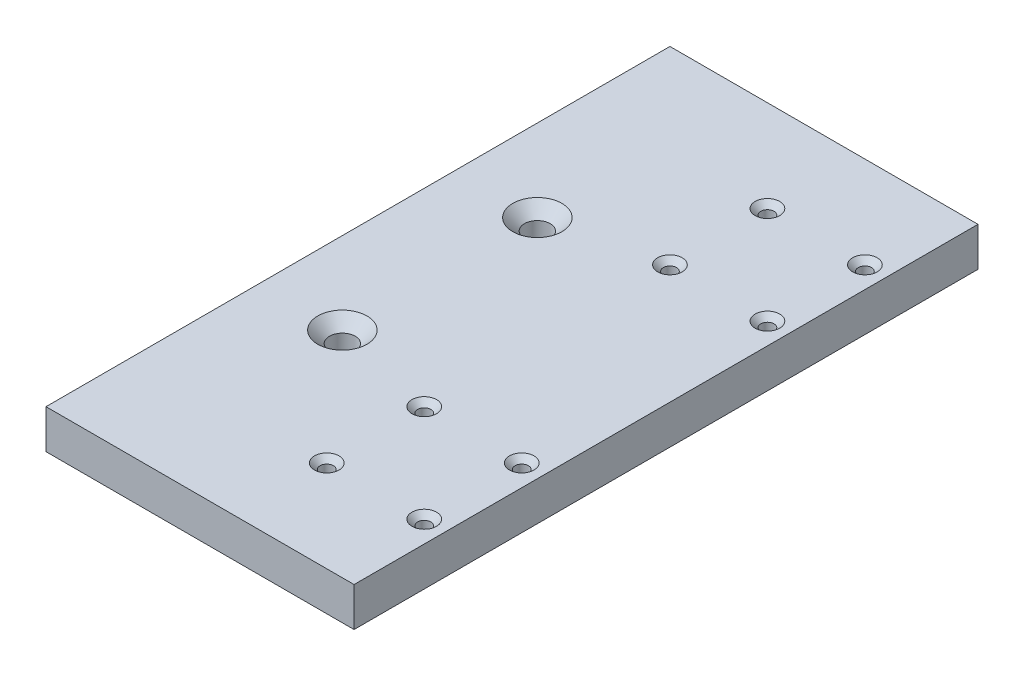
SolidWorks part; units mm, degrees
material "3.1355 (EN-AW 2024)"
ref_plane "Спереди" through (0, 0, 0) normal (0, 0, 1) x (1, 0, 0)
ref_plane "Сверху" through (0, 0, 0) normal (0, 1, 0) x (1, 0, 0)
ref_plane "Справа" through (0, 0, 0) normal (1, 0, 0) x (0, 0, -1)
sketch "Эскиз1" plane through (0, 0, 0) normal (0, 1, 0) x (1, 0, 0)
  line L1 (-39.5, 80) -> (39.5, 80)
  line L2 (-39.5, 80) -> (-39.5, -80)
  line L3 (-39.5, -80) -> (39.5, -80)
  line L4 (39.5, 80) -> (39.5, -80)
  line L5 (-39.5, 80) -> (39.5, -80) construction
  line L6 (-39.5, -80) -> (39.5, 80) construction
  point P0 (0, 0)
  dimension "D1" = 160
  dimension "D2" = 79
extrude "База" add sketch "Эскиз1" along normal blind 10
hole_wizard "Каретки M3" positions "Эскиз2" profile "Эскиз3" countersink size "M3" standard "DIN" end condition through all
sketch "Эскиз2" plane through (0, 10, 0) normal (0, 1, 0) x (1, 0, 0)
  line L0 (9, -31.5) -> (21.5, -31.5) construction
  line L1 (21.5, -31.5) -> (34, -31.5) construction
  line L2 (34, -31.5) -> (34, -56.5) construction
  line L5 (-50, 0) -> (50, 0) construction
  line L6 (34, 31.5) -> (34, 56.5) construction
  line L7 (21.5, 31.5) -> (34, 31.5) construction
  line L8 (9, 31.5) -> (21.5, 31.5) construction
  line L9 (39.5, -80) -> (39.5, 80) construction
  point P0 (9, -56.5)
  point P2 (34, -56.5)
  point P4 (34, -31.5)
  point P6 (9, -31.5)
  point P23 (9, 56.5)
  point P27 (9, 31.5)
  point P30 (34, 31.5)
  point P33 (34, 56.5)
  point P34 (9, 56.5)
  point P35 (34, -44)
  dimension "D1" = 25
  dimension "D2" = 25
  dimension "D3" = 44
  dimension "D4" = 18
sketch "Эскиз3" plane through (9, 10, 56.5) normal (1, 0, 0) x (0, 0, 1)
  line L0 (0, 0) -> (0, 10)
  line L1 (0, 10) -> (1.7, 10)
  line L2 (1.7, 10) -> (1.7, 1.45)
  line L3 (1.7, 1.45) -> (3.15, 0)
  line L5 (3.15, 0) -> (0, 0)
  line L6 (-1.7, 1.45) -> (-3.15, 0) construction
  line L11 (0, -6.35) -> (0, 107.95) construction
  dimension "Диаметр сквозного отверстия" = 3.4
  dimension "Глубина сквозного отверстия" = 10
  dimension "Диаметр передней зенковки" = 6.3
  dimension "Угол передней зенковки" = 90
hole_wizard "КреплениеПлиты-M6" positions "Эскиз6" profile "Эскиз7" countersink size "M6" standard "ISO" end condition through all
sketch "Эскиз6" plane through (0, 10, 0) normal (0, 1, 0) x (1, 0, 0)
  line L0 (-18.5, 25) -> (-18.5, 0) construction
  line L1 (-18.5, 0) -> (-18.5, -25) construction
  line L2 (39.5, -80) -> (39.5, 80) construction
  point P2 (-18.5, 25)
  point P5 (-18.5, -25)
  dimension "D1" = 58
  dimension "D2" = 25
sketch "Эскиз7" plane through (-18.5, 10, -25) normal (1, 0, 0) x (0, 0, 1)
  line L0 (0, 0) -> (0, 10)
  line L1 (0, 10) -> (3.3, 10)
  line L2 (3.3, 10) -> (3.3, 3)
  line L3 (3.3, 3) -> (6.3, 0)
  line L5 (6.3, 0) -> (0, 0)
  line L6 (-3.3, 3) -> (-6.3, 0) construction
  line L11 (0, -6.35) -> (0, 107.95) construction
  dimension "Диаметр сквозного отверстия" = 6.6
  dimension "Глубина сквозного отверстия" = 10
  dimension "Диаметр передней зенковки" = 12.6
  dimension "Угол передней зенковки" = 90
hole_wizard "Отверстие обработанное метчиком M61" positions "Эскиз8" profile "Эскиз10" tap size "M6" standard "DIN"
sketch "Эскиз8" plane through (-39.5, 0, 0) normal (-1, 0, 0) x (0, 0, 1)
  line L1 (-40, 5) -> (0, 5) construction
  line L2 (0, 5) -> (40, 5) construction
  line L5 (-80, 10) -> (-80, 0) construction
  point P0 (-40, 5)
  point P3 (40, 5)
  point P19 (-80, 5)
  dimension "D1" = 80
sketch "Эскиз10" plane through (-39.5, 5, -40) normal (0, 1, 0) x (0, 0, 1)
  line L0 (0, 0) -> (0, 36.5022)
  line L1 (0, 36.5022) -> (2.5, 35)
  line L2 (2.5, 35) -> (2.5, 0.525)
  line L3 (2.5, 0.525) -> (3.025, 0)
  line L5 (3.025, 0) -> (0, 0)
  line L6 (-2.5, 0.525) -> (-3.025, 0) construction
  line L10 (0, 36.5022) -> (-2.5, 35) construction
  line L11 (0, -6.35) -> (0, 107.95) construction
  dimension "Диаметр сверла" = 5
  dimension "Глубина сверла" = 35
  dimension "Диаметр передней зенковки" = 6.05
  dimension "Угол передней зенковки" = 90
  dimension "Угол заточки сверла" = 118
cosmetic thread "Отверстие резьбы1" parameters "D1"=30, "D2"=6
cosmetic thread "Отверстие резьбы2" parameters "D1"=30, "D2"=6
